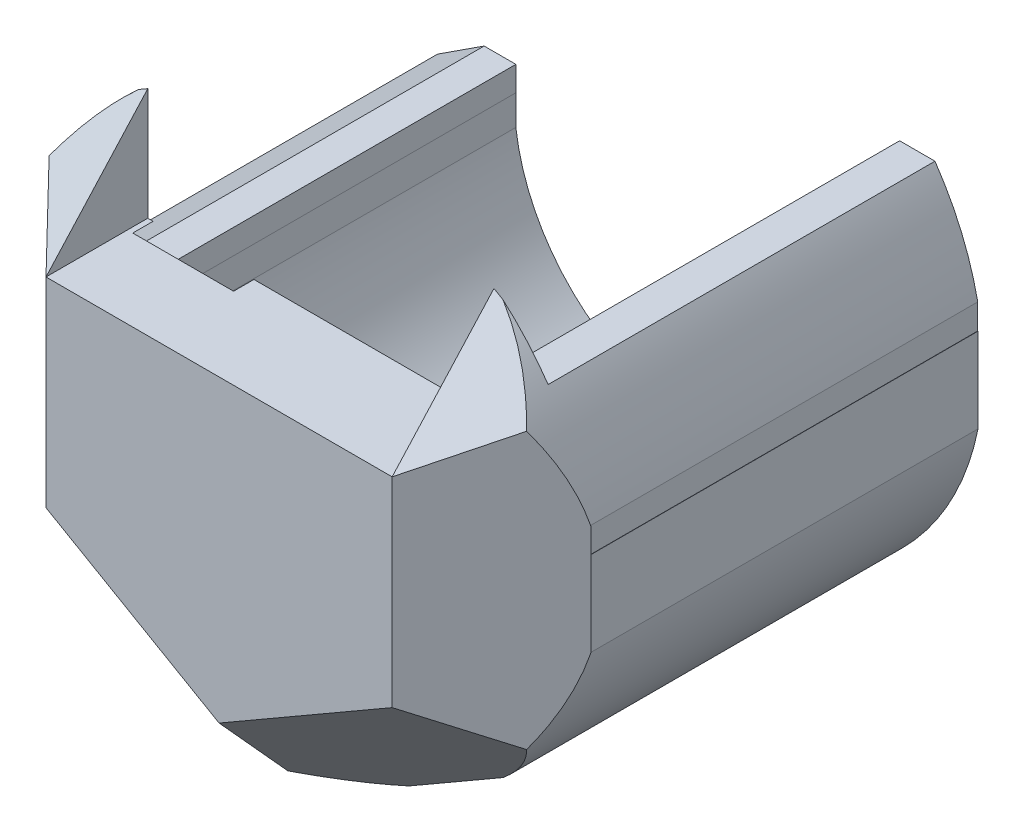
SolidWorks part; units mm, degrees
ref_plane "Front Plane" through (0, 0, 0) normal (0, 0, 1) x (1, 0, 0)
ref_plane "Top Plane" through (0, 0, 0) normal (0, 1, 0) x (1, 0, 0)
ref_plane "Right Plane" through (0, 0, 0) normal (1, 0, 0) x (0, 0, -1)
sketch "Sketch1" plane through (0, 0, 0) normal (0, 0, 1) x (1, 0, 0)
  line L0 (0, 0) -> (0, -18.4401) construction
  line L1 (9.4181, 0.2865) -> (9.4235, 1.4903)
  line L2 (0, 0) -> (0, 3.4105) construction
  line L3 (-9.4181, 0.2865) -> (-9.4235, 1.4903)
  line L5 (9.4235, 1.4903) -> (13.2729, 1.4903)
  line L6 (-9.4235, 1.4903) -> (-10.9817, 1.4903)
  line L7 (-9.4181, 0.2865) -> (-9.4247, -1.1937)
  line L8 (9.4181, 0.2865) -> (9.411, -1.2976)
  line L14 (-13.2729, 0) -> (-10.9817, 1.4903)
  line L17 (0, -15.3263) -> (13.2729, -7.6631)
  line L18 (13.2729, -7.6631) -> (13.2729, 1.4903)
  line L21 (-13.2729, 0) -> (-13.2729, -7.6631)
  line L22 (-13.2729, -7.6631) -> (0, -15.3263)
  line L25 (6.6365, 11.4947) -> (0, 15.3263) [skipped]
  line L26 (-6.6365, 11.4947) -> (-13.2729, 7.6631) [skipped]
  arc A1 (-9.4247, -1.1937) -> (9.411, -1.2976) centre (0, 0) ccw
  circle A3 centre (0, 0) radius 13.2729 construction
  dimension "D2" = 19
extrude "Boss-Extrude1" add sketch "Sketch1" along normal blind 19
sketch "Sketch2" plane through (0, 0, 19) normal (0, 0, 1) x (1, 0, 0)
  line L7 (0, -15.3263) -> (13.2729, -7.6631)
  line L8 (13.2729, -7.6631) -> (13.2729, 7.6631)
  line L9 (13.2729, 7.6631) -> (0, 15.3263)
  line L10 (0, 15.3263) -> (-13.2729, 7.6631)
  line L11 (-13.2729, 7.6631) -> (-13.2729, -7.6631)
  line L12 (-13.2729, -7.6631) -> (0, -15.3263)
  circle A0 centre (0, 0) radius 13.2729 construction
ref_plane "Plane1" through (0, 0, 24) normal (0, 0, 1) x (1, 0, 0)
sketch "Sketch3" plane through (0, 0, 24) normal (0, 0, 1) x (1, 0, 0)
  line L0 (0, 0) -> (0, 16.6901) construction
  line L1 (0, 0) -> (0, -15.3263) construction
  line L9 (0, -9.815) -> (8.5, -4.9075)
  line L10 (8.5, -4.9075) -> (8.5, 4.9075)
  line L11 (8.5, 4.9075) -> (0, 9.815)
  line L12 (0, 9.815) -> (-8.5, 4.9075)
  line L13 (-8.5, 4.9075) -> (-8.5, -4.9075)
  line L14 (-8.5, -4.9075) -> (0, -9.815)
  circle A0 centre (0, 0) radius 8.5 construction
  dimension "D1" = 17
loft "Loft1" add profiles "Sketch2", "Sketch3"
sketch "Sketch4" plane through (0, 0, 24) normal (0, 0, 1) x (1, 0, 0)
  line L0 (-8.5, 4.9075) -> (-8.5, 10.4188)
  line L1 (0, 15.3263) -> (-13.2729, 7.6631) construction
  line L2 (8.5, 4.9075) -> (8.5, 10.4188)
  line L3 (13.2729, 7.6631) -> (0, 15.3263) construction
  line L5 (-8.5, 4.9075) -> (8.5, 4.9075)
  line L6 (0, 15.3263) -> (-8.5, 10.4188)
  line L7 (0, 15.3263) -> (8.5, 10.4188)
extrude "Cut-Extrude1" cut sketch "Sketch4" against normal blind 5
sketch "Sketch5" plane through (0, 0, 19) normal (0, 0, -1) x (-1, 0, 0)
  circle A0 centre (5.7629, -0.0041) radius 5.5
extrude "Cut-Extrude2" cut sketch "Sketch5" against normal blind 1
sketch "Sketch6" plane through (0, 1.4903, 0) normal (0, 1, 0) x (1, 0, 0)
  line L0 (13.2729, -9.5) -> (9.411, -9.5) construction
  line L1 (13.2729, -19) -> (13.2729, 0) construction
  line L2 (9.411, -19) -> (9.411, 0) construction
  line L4 (13.2604, -19) -> (9.4235, -19)
  line L5 (13.2604, -19) -> (13.2604, 0)
  line L6 (13.2604, 0) -> (9.4235, 0)
  line L7 (9.4235, -19) -> (9.4235, 0)
  line L8 (13.2604, -19) -> (9.4235, 0) construction
  line L9 (13.2604, 0) -> (9.4235, -19) construction
  point P6 (11.342, -9.5)
extrude "Boss-Extrude2" add sketch "Sketch6" along normal up to vertex (6.1728 mm away) up to point (13.2729, 7.6631, 19)
sketch "Sketch7" plane through (0, 0, 0) normal (0, 0, -1) x (-1, 0, 0)
  line L1 (13.5382, 0) -> (15.3263, 0)
  line L2 (-13.5382, 0) -> (-15.3263, 0)
  line L3 (15.3263, 0) -> (0, 0) construction
  arc A0 (-13.5382, 0) -> (13.5382, 0) centre (0, 0) ccw
  arc A1 (-15.3263, 0) -> (15.3263, 0) centre (0, 0) ccw
extrude "Cut-Extrude3" cut sketch "Sketch7" against normal up to vertex (19 mm away)
sketch "Sketch8" plane through (0, 0, 19) normal (0, 0, -1) x (-1, 0, 0)
  circle A0 centre (0, 0) radius 13.5382
  circle A1 centre (0, 0) radius 15.3263
extrude "Cut-Extrude4" cut sketch "Sketch8" against normal blind 20
sketch "Sketch9" plane through (0, 0, 19) normal (0, 0, 1) x (1, 0, 0)
  circle A0 centre (0, 0) radius 13.5382
  circle A1 centre (0, 0) radius 15.3155
extrude "Cut-Extrude5" cut sketch "Sketch9" against normal blind 20
